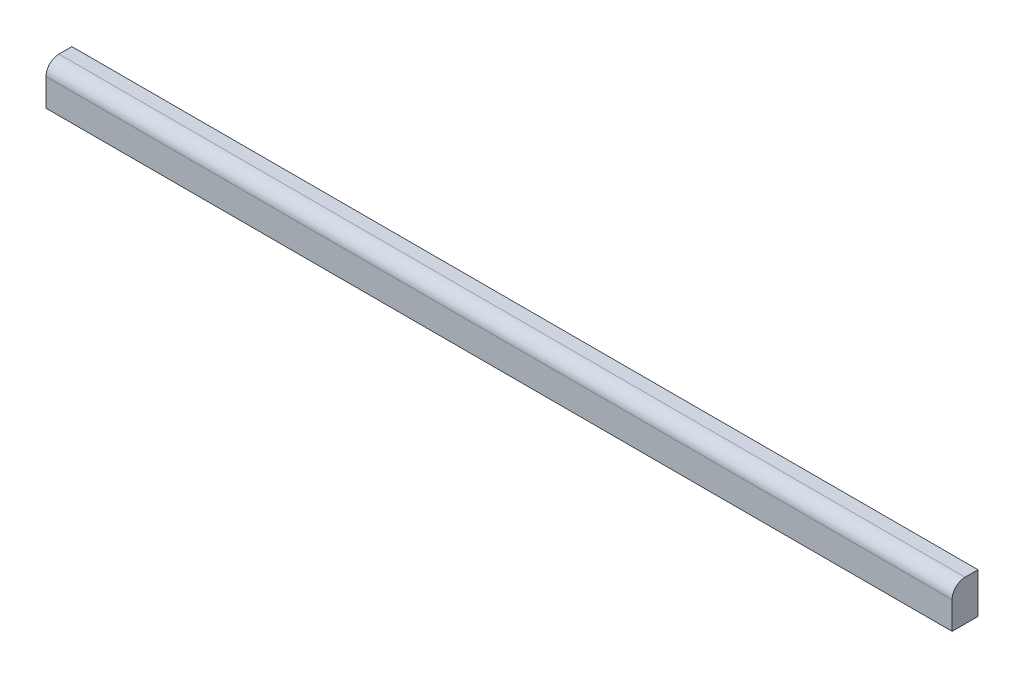
SolidWorks part; units mm, degrees
ref_plane "Front Plane" through (0, 0, 0) normal (0, 0, 1) x (1, 0, 0)
ref_plane "Top Plane" through (0, 0, 0) normal (0, 1, 0) x (1, 0, 0)
ref_plane "Right Plane" through (0, 0, 0) normal (1, 0, 0) x (0, 0, -1)
other "Bounding Box"
ref_plane "Default Plane" through (-280, 0, 0) normal (0, 1, 0) x (1, 0, 0)
sketch "Sketch1" plane through (0, 0, 0) normal (0, 0, 1) x (1, 0, 0)
  line L1 (280, 0) -> (-280, 0)
  line L2 (280, 0) -> (280, 25)
  line L3 (280, 25) -> (-280, 25)
  line L4 (-280, 0) -> (-280, 25)
  point P7 (0, 0)
  dimension "D1" = 560
  dimension "D2" = 25
extrude "Boss-Extrude1" add sketch "Sketch1" along normal blind 16
fillet "Fillet1" radius 8 1 edges at (0, 25, 16)
